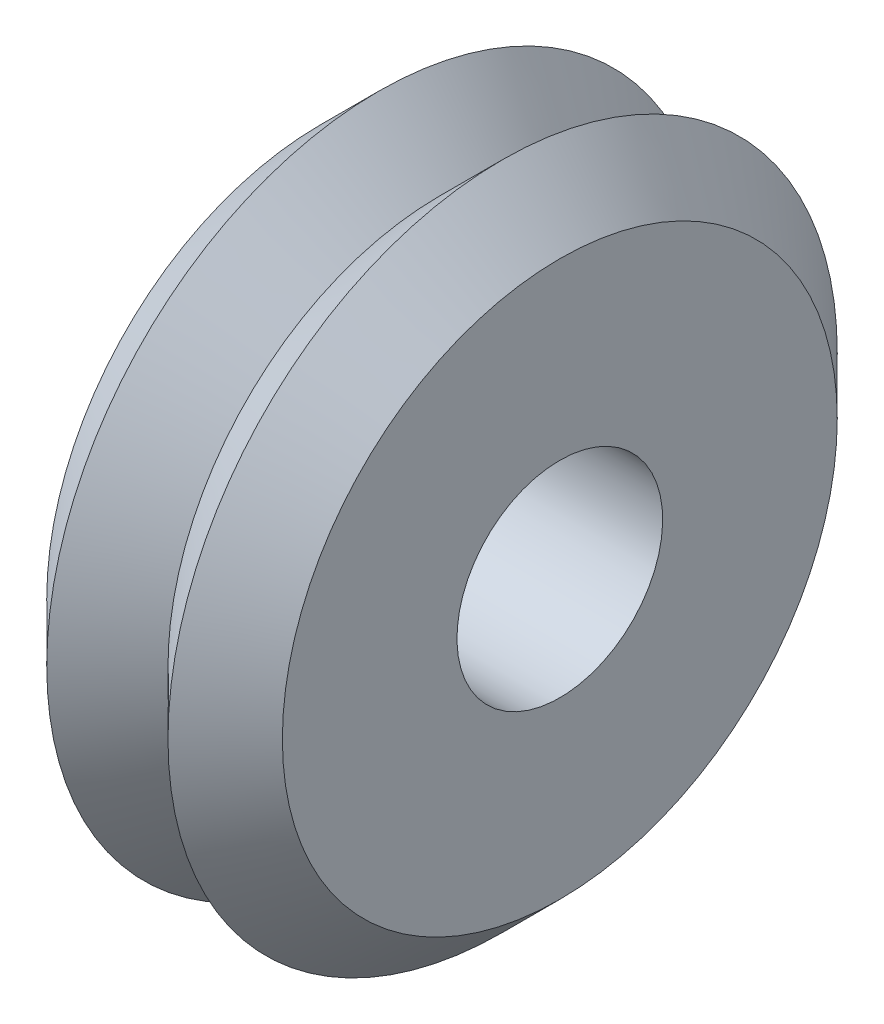
SolidWorks part; units mm, degrees
ref_plane "Front Plane" through (0, 0, 0) normal (0, 0, 1) x (1, 0, 0)
ref_plane "Top Plane" through (0, 0, 0) normal (0, 1, 0) x (1, 0, 0)
ref_plane "Right Plane" through (0, 0, 0) normal (1, 0, 0) x (0, 0, -1)
sketch "Sketch1" plane through (0, 0, 0) normal (0, 0, 1) x (1, 0, 0)
  line L0 (0, 0) -> (2.7114, 2.7114)
  line L1 (2.7114, 2.7114) -> (5.5181, -0.0953)
  line L2 (5.5181, -0.0953) -> (8.4518, 2.8385)
  line L3 (8.4518, 2.8385) -> (11.0998, 0.1905)
  line L4 (11.0998, 0.1905) -> (11.0998, -12.6556)
  line L5 (11.0998, -12.6556) -> (0, -12.6556)
  line L6 (0, -12.6556) -> (0, 0)
  dimension "D1" = 11.0998
  dimension "D2" = 90
  dimension "D3" = 90
  dimension "D4" = 5.7404
  dimension "D5" = 15.367
revolve "Revolve1" add sketch "Sketch1" angle 360 about L5
sketch "Sketch2" plane through (11.0998, 0, 0) normal (1, 0, 0) x (0, 0, -1)
  circle A0 centre (0, -12.6556) radius 4.7625
  dimension "D1" = 9.525
extrude "Cut-Extrude1" cut sketch "Sketch2" against normal through all
